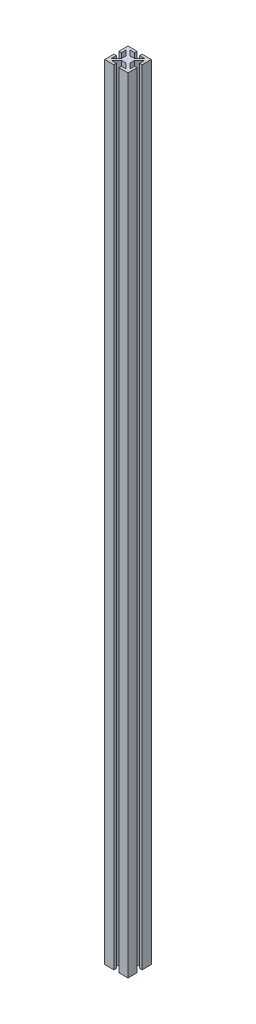
SolidWorks part; units mm, degrees
ref_plane "Front Plane" through (0, 0, 0) normal (0, 0, 1) x (1, 0, 0)
ref_plane "Top Plane" through (0, 0, 0) normal (0, 1, 0) x (1, 0, 0)
ref_plane "Right Plane" through (0, 0, 0) normal (1, 0, 0) x (0, 0, -1)
sketch "Sketch2" plane through (0.5947, 0, 0.5947) normal (0, 1, 0) x (1, 0, 0)
  line L0 (-0.5947, 0.5947) -> (-0.5947, 20.2394) construction
  line L1 (-0.5947, 0.5947) -> (-20.2394, 0.5947) construction
  line L2 (-0.5947, 0.5947) -> (-20.2394, 20.2394) construction
  line L3 (-19.6447, 19.6447) -> (-4.6587, 19.6447)
  line L4 (-4.6587, 19.6447) -> (-4.6587, 15.5807)
  line L5 (-4.6587, 15.5807) -> (-12.707, 15.5807)
  line L6 (-12.707, 15.5807) -> (-4.4774, 7.3511)
  line L7 (-4.4774, 7.3511) -> (3.288, 7.3511)
  line L8 (-19.6447, 19.6447) -> (-19.6447, 4.6587)
  line L9 (-19.6447, 4.6587) -> (-15.5807, 4.6587)
  line L10 (-15.5807, 4.6587) -> (-15.5807, 12.707)
  line L11 (-15.5807, 12.707) -> (-7.3511, 4.4774)
  line L12 (-7.3511, 4.4774) -> (-7.3511, -3.288)
  line L13 (-4.4774, -6.1617) -> (3.288, -6.1617)
  line L14 (-12.707, -14.3913) -> (-4.4774, -6.1617)
  line L15 (-4.6587, -14.3913) -> (-12.707, -14.3913)
  line L16 (-4.6587, -18.4553) -> (-4.6587, -14.3913)
  line L17 (-19.6447, -18.4553) -> (-4.6587, -18.4553)
  line L18 (-19.6447, -18.4553) -> (-19.6447, -3.4693)
  line L19 (-19.6447, -3.4693) -> (-15.5807, -3.4693)
  line L20 (-15.5807, -3.4693) -> (-15.5807, -11.5176)
  line L21 (-15.5807, -11.5176) -> (-7.3511, -3.288)
  line L22 (11.5176, 15.5807) -> (3.288, 7.3511)
  line L23 (3.4693, 15.5807) -> (11.5176, 15.5807)
  line L24 (3.4693, 19.6447) -> (3.4693, 15.5807)
  line L25 (18.4553, 19.6447) -> (3.4693, 19.6447)
  line L26 (18.4553, 19.6447) -> (18.4553, 4.6587)
  line L27 (18.4553, 4.6587) -> (14.3913, 4.6587)
  line L28 (14.3913, 4.6587) -> (14.3913, 12.707)
  line L29 (14.3913, 12.707) -> (6.1617, 4.4774)
  line L30 (6.1617, 4.4774) -> (6.1617, -3.288)
  line L31 (14.3913, -11.5176) -> (6.1617, -3.288)
  line L32 (14.3913, -3.4693) -> (14.3913, -11.5176)
  line L33 (18.4553, -3.4693) -> (14.3913, -3.4693)
  line L34 (18.4553, -18.4553) -> (18.4553, -3.4693)
  line L35 (18.4553, -18.4553) -> (3.4693, -18.4553)
  line L36 (3.4693, -18.4553) -> (3.4693, -14.3913)
  line L37 (3.4693, -14.3913) -> (11.5176, -14.3913)
  line L38 (11.5176, -14.3913) -> (3.288, -6.1617)
  point P26 (-7.3511, 0.5947)
  point P27 (-0.5947, 7.3511)
  point P44 (-0.5947, -6.1617)
  dimension "D1" = 38.1
  dimension "D2" = 8.128
  dimension "D3" = 13.5128
  dimension "D4" = 4.064
  dimension "D5" = 4.064
extrude "Boss-Extrude1" add sketch "Sketch2" along normal blind 1282.7
other "1515<1>"
